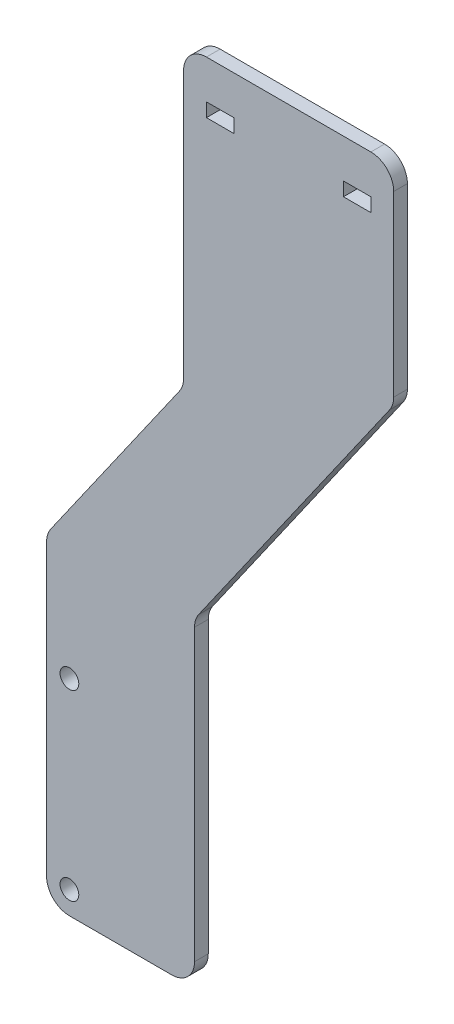
SolidWorks part; units mm, degrees
ref_plane "Front Plane" through (0, 0, 0) normal (0, 0, 1) x (1, 0, 0)
ref_plane "Top Plane" through (0, 0, 0) normal (0, 1, 0) x (1, 0, 0)
ref_plane "Right Plane" through (0, 0, 0) normal (1, 0, 0) x (0, 0, -1)
sketch "Sketch1" plane through (0, 0, 0) normal (0, 0, 1) x (1, 0, 0)
  line L0 (-43.6038, -10.8444) -> (-76, -10.8444)
  line L1 (-76, -10.8444) -> (-76, 59.1556)
  line L3 (-46, 102) -> (-46, 167)
  line L4 (-46, 167) -> (0, 167)
  line L5 (0, 167) -> (0, 121.4283)
  line L6 (-71, 34.1556) -> (-71, -18.7631) construction
  line L7 (-23, 167) -> (-23, 157) construction
  line L8 (-23, 157) -> (-1.1451, 157) construction
  line L9 (-35, 158.5) -> (-35, 155.5)
  line L10 (-11, 158.5) -> (-5, 158.5)
  line L11 (-11, 158.5) -> (-11, 155.5)
  line L12 (-11, 155.5) -> (-5, 155.5)
  line L13 (-5, 158.5) -> (-5, 155.5)
  line L14 (-11, 158.5) -> (-5, 155.5) construction
  line L15 (-11, 155.5) -> (-5, 158.5) construction
  line L16 (-35, 155.5) -> (-41, 155.5)
  line L17 (-41, 158.5) -> (-41, 155.5)
  line L18 (-35, 158.5) -> (-41, 158.5)
  line L19 (-46, 102) -> (-76, 59.1556)
  line L21 (0, 102) -> (-46, 102) construction
  line L22 (-43.6038, 39.7273) -> (-43.6038, -10.8444)
  line L23 (-76, 59.1556) -> (-43.6038, 59.1556) construction
  line L24 (-43.6038, 39.7273) -> (-43.6038, 59.1556)
  line L25 (-43.6038, 59.1556) -> (0, 121.4283)
  circle A0 centre (-71, 34.1556) radius 2.05
  circle A1 centre (-71, -5.8444) radius 2.05
  point P15 (-8, 157)
  dimension "D1" = 4.1
  dimension "D3" = 5
  dimension "D7" = 40
  dimension "D2" = 5
  dimension "D4" = 25
  dimension "D5" = 46
  dimension "D6" = 145
  dimension "D8" = 70
  dimension "D9" = 6
  dimension "D10" = 3
  dimension "D11" = 15
  dimension "D12" = 10
  dimension "D13" = 65
extrude "Boss-Extrude1" add sketch "Sketch1" along normal blind 3
fillet "Fillet1" radius 5 8 edges at (-46, 167, 1.5) (0, 167, 1.5) (-76, -10.8444, 1.5) (-46, 102, 1.5) (-76, 59.1556, 1.5) (-43.6038, -10.8444, 1.5) (-43.6038, 59.1556, 1.5) (0, 121.4283, 1.5)
